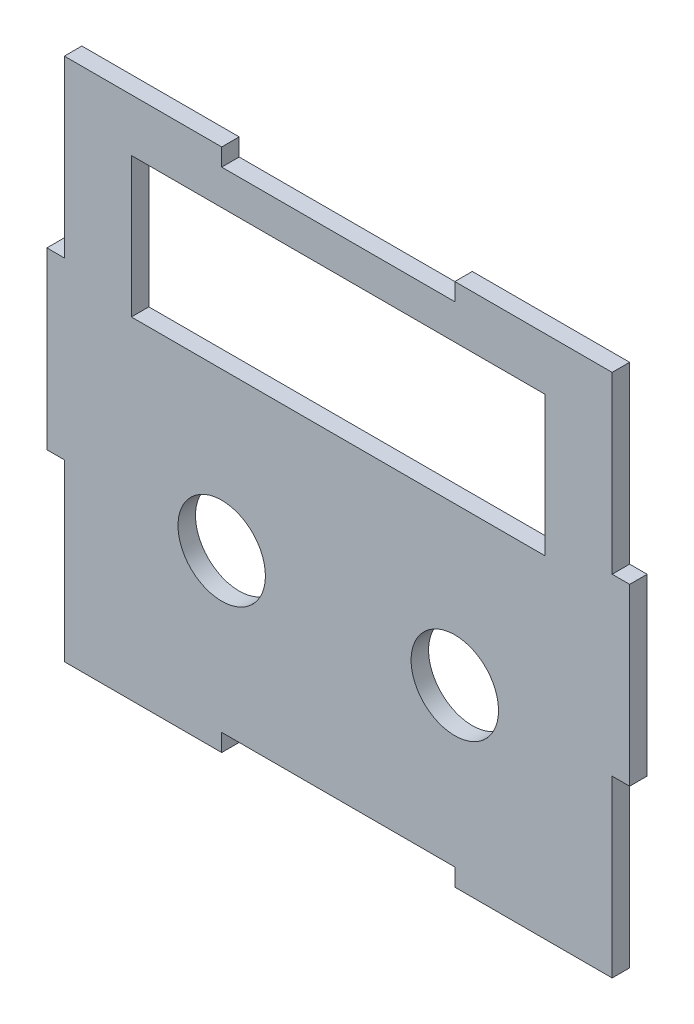
SolidWorks part; units mm, degrees
ref_plane "Plan de face" through (0, 0, 0) normal (0, 0, 1) x (1, 0, 0)
ref_plane "Plan de dessus" through (0, 0, 0) normal (0, 1, 0) x (1, 0, 0)
ref_plane "Plan de droite" through (0, 0, 0) normal (1, 0, 0) x (0, 0, -1)
sketch "Esquisse1" plane through (0, 0, 0) normal (0, 0, 1) x (1, 0, 0)
  line L1 (-60.0385, 25.677) -> (39.9615, 25.677)
  line L2 (-60.0385, 25.677) -> (-60.0385, -64.323)
  line L3 (-60.0385, -64.323) -> (39.9615, -64.323)
  line L4 (39.9615, 25.677) -> (39.9615, -64.323)
  line L5 (-45.5385, 16.6603) -> (25.4615, 16.6603)
  line L6 (-45.5385, 16.6603) -> (-45.5385, -7.3397)
  line L7 (-45.5385, -7.3397) -> (25.4615, -7.3397)
  line L8 (25.4615, 16.6603) -> (25.4615, -7.3397)
  circle A0 centre (-30.0385, -34.323) radius 7.5
  circle A1 centre (9.9615, -34.323) radius 7.5
  dimension "D3" = 15
  dimension "D4" = 15
  dimension "D1" = 100
  dimension "D2" = 90
  dimension "D5" = 24
  dimension "D6" = 71
  dimension "D7" = 14.5
  dimension "D8" = 40
  dimension "D9" = 30
  dimension "D10" = 30
extrude "Boss.-Extru.1" add sketch "Esquisse1" along normal blind 3
sketch "Esquisse2" plane through (0, 0, 3) normal (0, 0, 1) x (1, 0, 0)
  line L0 (39.9615, 25.677) -> (-60.0385, 25.677) construction
  line L1 (-30.0385, 25.677) -> (9.9615, 25.677)
  line L2 (-30.0385, 25.677) -> (-30.0385, 22.677)
  line L3 (-30.0385, 22.677) -> (9.9615, 22.677)
  line L4 (9.9615, 25.677) -> (9.9615, 22.677)
  line L5 (-60.0385, 25.677) -> (-60.0385, -64.323) construction
  line L6 (-60.0385, 25.677) -> (-57.0385, 25.677)
  line L7 (-60.0385, 25.677) -> (-60.0385, -4.323)
  line L8 (-60.0385, -4.323) -> (-57.0385, -4.323)
  line L9 (-57.0385, 25.677) -> (-57.0385, -4.323)
  line L10 (-60.0385, -34.323) -> (-57.0385, -34.323)
  line L11 (-60.0385, -34.323) -> (-60.0385, -64.323)
  line L12 (-60.0385, -64.323) -> (-57.0385, -64.323)
  line L13 (-57.0385, -34.323) -> (-57.0385, -64.323)
  line L14 (-60.0385, -64.323) -> (39.9615, -64.323) construction
  line L15 (39.9615, -64.323) -> (39.9615, 25.677) construction
  line L16 (-30.0385, -64.323) -> (9.9615, -64.323)
  line L17 (-30.0385, -64.323) -> (-30.0385, -61.323)
  line L18 (-30.0385, -61.323) -> (9.9615, -61.323)
  line L19 (9.9615, -64.323) -> (9.9615, -61.323)
  line L20 (36.9615, -64.323) -> (39.9615, -64.323)
  line L21 (36.9615, -64.323) -> (36.9615, -34.323)
  line L22 (36.9615, -34.323) -> (39.9615, -34.323)
  line L23 (39.9615, -64.323) -> (39.9615, -34.323)
  line L25 (36.9615, 25.677) -> (39.9615, 25.677)
  line L26 (36.9615, 25.677) -> (36.9615, -4.323)
  line L27 (36.9615, -4.323) -> (39.9615, -4.323)
  line L28 (39.9615, 25.677) -> (39.9615, -4.323)
  dimension "D1" = 3
  dimension "D2" = 30
  dimension "D3" = 40
  dimension "D4" = 27
extrude "Enlèv. mat.-Extru.1" cut sketch "Esquisse2" against normal up to next
